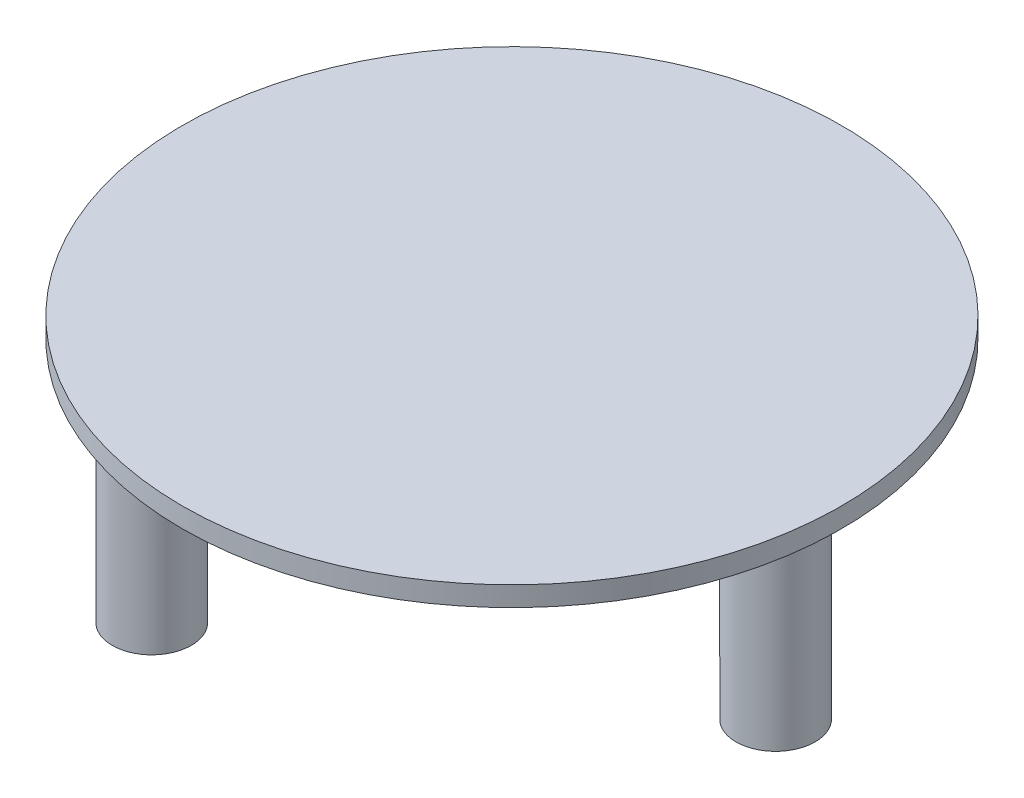
SolidWorks part; units mm, degrees
ref_plane "Front Plane" through (0, 0, 0) normal (0, 0, 1) x (1, 0, 0)
ref_plane "Top Plane" through (0, 0, 0) normal (0, 1, 0) x (1, 0, 0)
ref_plane "Right Plane" through (0, 0, 0) normal (1, 0, 0) x (0, 0, -1)
sketch "Sketch1" plane through (0, 0, 0) normal (0, 1, 0) x (1, 0, 0)
  circle A0 centre (0, 0) radius 250
  dimension "D1" = 500
extrude "Boss-Extrude1" add sketch "Sketch1" along normal blind 15
sketch "Sketch2" plane through (0, 0, 0) normal (0, -1, 0) x (1, 0, 0)
  circle A0 centre (200, 0) radius 30
extrude "Boss-Extrude2" add sketch "Sketch2" along normal blind 150
pattern_circular "CirPattern1" count 3 over 360 about axis through (0, 0, 0) along (0, 1, 0) of "Boss-Extrude2"
